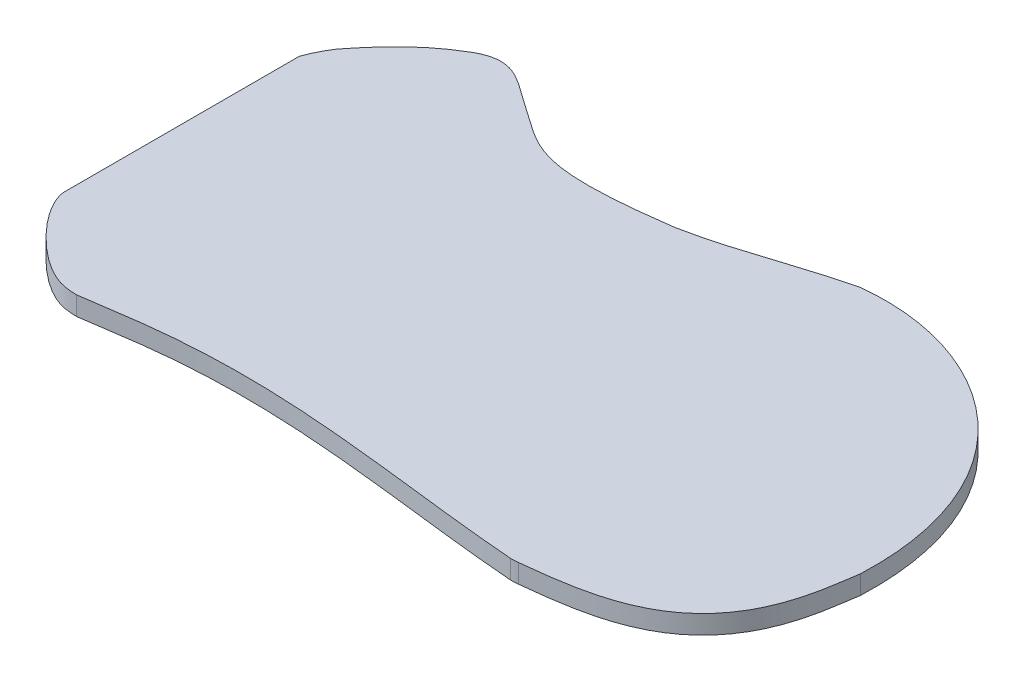
SolidWorks part; units mm, degrees
ref_plane "Front Plane" through (0, 0, 0) normal (0, 0, 1) x (1, 0, 0)
ref_plane "Top Plane" through (0, 0, 0) normal (0, 1, 0) x (1, 0, 0)
ref_plane "Right Plane" through (0, 0, 0) normal (1, 0, 0) x (0, 0, -1)
sketch "Sketch1" plane through (0, 0, 0) normal (0, 1, 0) x (1, 0, 0)
  line L0 (-78.6109, 24.9032) -> (-78.6109, -25.142)
  line L1 (78.526, -10.9955) -> (-78.6109, -10.9955) construction
  line L2 (-77.6109, 24.7348) -> (-77.6109, -25.142)
  line L3 (78.526, -11.9955) -> (-78.6109, -11.9955)
  arc A0 (37.4157, -46.3273) -> (39.1437, -46.2432) centre (37.8097, -36.6353) ccw
  arc A1 (37.4725, -45.3288) -> (39.0215, -45.2505) centre (37.8097, -36.6353) ccw
  spline S0 degree 3 poles (-77.6109, -25.142) (-77.6103, -25.4) (-77.563, -25.903) (-77.2897, -26.9857) (-76.6417, -28.5306) (-75.4978, -30.4481) (-73.6058, -33.039) (-70.8033, -36.112) (-67.3274, -39.127) (-64.1402, -41.244) (-61.4556, -42.4361) (-59.2812, -42.8778) (-58.0256, -42.9092) (-57.3728, -42.9466) knots 0.000484 0.000484 0.000484 0.000484 0.031521 0.062558 0.124632 0.186706 0.248781 0.372929 0.497077 0.621225 0.745373 0.869521 0.993669 0.993669 0.993669 0.993669
  spline S1 degree 3 poles (-57.3728, -42.9466) (-57.1306, -42.9172) (-56.6559, -42.8572) (-55.6329, -42.7168) (-54.2832, -42.5176) (-52.5297, -42.2482) (-50.0282, -41.8652) (-46.6003, -41.367) (-42.0363, -40.8111) (-37.0514, -40.3559) (-29.8812, -39.9429) (-20.0109, -39.8766) (-6.9377, -40.6174) (4.791, -41.8163) (14.5692, -42.9593) (22.0672, -43.8389) (29.7001, -44.6718) (34.8871, -45.1373) (37.4725, -45.3288) knots 0.000538 0.000538 0.000538 0.000538 0.016152 0.031766 0.062993 0.094221 0.125449 0.187904 0.250359 0.312815 0.37527 0.50018 0.625091 0.750001 0.812457 0.874912 0.937367 0.999822 0.999822 0.999822 0.999822
  spline S2 degree 3 poles (39.0215, -45.2505) (40.5541, -45.0873) (43.6362, -44.7445) (49.6297, -43.8727) (56.6431, -42.2158) (63.7646, -38.9137) (69.3225, -34.2155) (72.596, -29.3087) (74.4639, -25.0567) (75.5267, -21.803) (76.2971, -18.6022) (76.7457, -16.0939) (77.026, -14.2578) (77.207, -12.9947) (77.3723, -11.8407) (77.4763, -11.2132) (77.5311, -10.8821) knots -0.000309 -0.000309 -0.000309 -0.000309 0.063093 0.126495 0.253299 0.380104 0.506908 0.633712 0.697114 0.760516 0.823918 0.88732 0.919021 0.950722 0.982423 1.014124 1.014124 1.014124 1.014124
  spline S3 degree 3 poles (77.5311, -10.8821) (77.5748, -9.7665) (77.6099, -7.5074) (77.4888, -4.2729) (77.2058, -1.1252) (76.6195, 2.9373) (75.5088, 7.7538) (72.9895, 14.9059) (68.5668, 22.78) (61.5957, 30.4634) (53.3357, 36.3146) (44.1583, 40.2648) (34.4498, 42.2506) (27.8575, 42.2059) (24.6064, 41.8434) knots 0.000169 0.000169 0.000169 0.000169 0.031414 0.062658 0.093902 0.125147 0.187635 0.250124 0.375101 0.500079 0.625056 0.750034 0.875011 0.999988 0.999988 0.999988 0.999988
  spline S4 degree 3 poles (24.6064, 41.8434) (19.4417, 40.5996) (11.8686, 38.1019) (1.7069, 34.9414) (-3.4909, 33.6615) (-6.1131, 33.1605) knots 0.000659 0.000659 0.000659 0.000659 0.498067 0.746772 0.995476 0.995476 0.995476 0.995476
  spline S5 degree 3 poles (-6.1131, 33.1605) (-7.1417, 33.0163) (-9.1825, 32.742) (-13.4171, 32.237) (-18.6364, 31.7654) (-24.3553, 31.6023) (-29.2844, 31.96) (-33.4204, 32.9216) (-36.3715, 34.2616) (-38.6497, 35.6481) (-40.393, 36.836) (-41.9608, 37.95) (-43.3176, 38.8994) (-44.0701, 39.4107) (-44.4391, 39.6587) knots -0.000196 -0.000196 -0.000196 -0.000196 0.062587 0.12537 0.250936 0.376501 0.502067 0.627632 0.753198 0.815981 0.878764 0.941546 0.972938 1.004329 1.004329 1.004329 1.004329
  spline S6 degree 3 poles (-44.4391, 39.6587) (-44.6983, 39.8375) (-45.2219, 40.2027) (-46.2044, 40.9033) (-47.345, 41.7292) (-48.5998, 42.6198) (-50.1509, 43.6513) (-51.9146, 44.6189) (-53.8615, 45.2294) (-55.7055, 45.3275) (-57.1648, 45.051) (-58.2486, 44.6839) (-59.0003, 44.3616) (-59.6837, 44.0129) (-60.0375, 43.8061) (-60.2239, 43.694) knots -0.002497 -0.002497 -0.002497 -0.002497 0.029066 0.060629 0.123754 0.18688 0.250006 0.376257 0.502509 0.62876 0.755012 0.818137 0.881263 0.944389 1.007515 1.007515 1.007515 1.007515
  spline S7 degree 3 poles (-78.6109, -25.142) (-78.6097, -25.7822) (-78.3711, -27.0076) (-77.5216, -29.0127) (-76.3076, -31.0396) (-74.3365, -33.7283) (-71.4439, -36.8883) (-67.8634, -39.9802) (-64.5529, -42.1647) (-61.6917, -43.4202) (-59.6968, -43.8088) (-58.2959, -43.9054) (-57.6656, -43.9305) (-57.3419, -43.9502) knots 0.000409 0.000409 0.000409 0.000409 0.062843 0.125276 0.18771 0.250143 0.375011 0.499878 0.624745 0.749612 0.874479 0.936913 0.999346 0.999346 0.999346 0.999346
  spline S8 degree 3 poles (-57.3419, -43.9502) (-57.0965, -43.9206) (-56.6141, -43.8604) (-55.5847, -43.7202) (-54.2292, -43.5208) (-52.4771, -43.2519) (-49.983, -42.8696) (-46.5727, -42.3725) (-42.0367, -41.817) (-37.0824, -41.3612) (-29.9535, -40.9457) (-20.1287, -40.874) (-7.0907, -41.608) (4.6318, -42.8047) (14.4219, -43.9489) (21.9389, -44.8307) (29.5994, -45.6669) (34.8166, -46.135) (37.4157, -46.3273) knots -0.001373 -0.001373 -0.001373 -0.001373 0.014273 0.029919 0.06121 0.092502 0.123794 0.186377 0.24896 0.311543 0.374127 0.499293 0.62446 0.749626 0.81221 0.874793 0.937376 0.99996 0.99996 0.99996 0.99996
  spline S9 degree 3 poles (39.1437, -46.2432) (40.686, -46.0789) (43.7818, -45.7344) (49.848, -44.8507) (56.9964, -43.16) (64.3453, -39.7462) (70.1244, -34.8409) (73.5118, -29.7304) (75.4294, -25.3355) (76.5134, -21.9918) (77.2941, -18.7213) (77.7459, -16.1748) (78.0266, -14.3264) (78.2075, -13.0606) (78.3702, -11.9307) (78.4738, -11.3105) (78.5279, -10.984) knots -0.000086 -0.000086 -0.000086 -0.000086 0.063428 0.126941 0.253967 0.380993 0.50802 0.635046 0.698559 0.762072 0.825585 0.889098 0.920855 0.952612 0.984368 1.016125 1.016125 1.016125 1.016125
  spline S10 degree 3 poles (78.5279, -10.984) (78.5733, -9.8502) (78.6109, -7.5559) (78.4906, -4.2601) (78.2049, -1.0549) (77.6104, 3.0871) (76.4803, 8.0028) (73.9108, 15.31) (69.3901, 23.3646) (62.2582, 31.2245) (53.8088, 37.2052) (44.4261, 41.2372) (34.4991, 43.2588) (27.7571, 43.2053) (24.4331, 42.8302) knots -0.000407 -0.000407 -0.000407 -0.000407 0.03088 0.062166 0.093453 0.12474 0.187314 0.249888 0.375035 0.500183 0.62533 0.750478 0.875625 1.000773 1.000773 1.000773 1.000773
  spline S11 degree 3 poles (24.4331, 42.8302) (21.8301, 42.2051) (16.6685, 40.7402) (6.525, 37.4536) (-1.0744, 35.1413) (-6.2764, 34.1474) knots -0.001281 -0.001281 -0.001281 -0.001281 0.247714 0.49671 0.9947 0.9947 0.9947 0.9947
  spline S12 degree 3 poles (-6.2764, 34.1474) (-7.3001, 34.0039) (-9.3317, 33.7312) (-13.542, 33.2295) (-18.7181, 32.7628) (-24.3556, 32.604) (-29.1564, 32.9561) (-33.1061, 33.8787) (-35.9015, 35.1472) (-38.1022, 36.4854) (-39.8157, 37.6526) (-41.3786, 38.7631) (-42.7458, 39.7198) (-43.5043, 40.2353) (-43.8763, 40.4853) knots 0.000305 0.000305 0.000305 0.000305 0.063048 0.125791 0.251276 0.376761 0.502247 0.627732 0.753218 0.815961 0.878703 0.941446 0.972817 1.004189 1.004189 1.004189 1.004189
  spline S13 degree 3 poles (-43.8763, 40.4853) (-44.1324, 40.662) (-44.6496, 41.0228) (-45.6222, 41.7163) (-46.7618, 42.5415) (-48.0307, 43.4423) (-49.6264, 44.5037) (-51.4979, 45.535) (-53.6685, 46.2221) (-55.7733, 46.3353) (-57.4106, 46.0235) (-58.6015, 45.6208) (-59.4227, 45.2686) (-60.0246, 44.9622) (-60.4597, 44.7184) (-60.6399, 44.6107) (-60.7341, 44.5541) knots -0.002294 -0.002294 -0.002294 -0.002294 0.029245 0.060783 0.12386 0.186936 0.250013 0.376167 0.50232 0.628473 0.754627 0.817704 0.88078 0.943857 0.975396 1.006934 1.006934 1.006934 1.006934
  spline S14 degree 3 poles (-60.7341, 44.5541) (-61.1687, 44.2998) (-62.0358, 43.7712) (-63.676, 42.6889) (-66.3643, 40.7074) (-69.6969, 37.7112) (-72.4782, 34.663) (-74.193, 32.5981) (-75.1195, 31.4458) (-75.5587, 30.8903) (-75.7803, 30.6092) knots 0.000427 0.000427 0.000427 0.000427 0.063268 0.126109 0.251792 0.503158 0.754524 0.880206 0.943048 1.005889 1.005889 1.005889 1.005889
  spline S15 degree 3 poles (-60.2239, 43.694) (-60.6474, 43.4463) (-61.4924, 42.9314) (-63.0906, 41.8773) (-65.7124, 39.9465) (-68.9709, 37.0199) (-71.6981, 34.0358) (-73.6437, 31.6948) (-74.5236, 30.5881) (-74.9696, 30.0223) knots 0.000174 0.000174 0.000174 0.000174 0.062881 0.125589 0.251004 0.501833 0.752662 0.878077 1.003492 1.003492 1.003492 1.003492
  spline S16 degree 3 poles (-74.9696, 30.0223) (-75.5195, 29.1919) (-76.5302, 27.448) (-77.2874, 25.6577) (-77.6109, 24.7348) knots 0.499549 0.499549 0.499549 0.499549 0.499766 0.499983 0.499983 0.499983 0.499983
  spline S17 degree 3 poles (-75.7803, 30.6092) (-76.3738, 29.7162) (-77.4602, 27.8403) (-78.2688, 25.9015) (-78.6109, 24.9032) knots 0.499546 0.499546 0.499546 0.499546 0.49977 0.499995 0.499995 0.499995 0.499995
  point P0 (0.0094, -10.9955)
extrude "Boss-Extrude2" add sketch "Sketch1" along normal blind 4 contours L1 S2 S3 S4 S5 S6 S15 S16 L2 | S2 L1 L2 L3 | A1 S2 L3 L2 S0 S1
ref_plane "Plane1" through (0, 0, -24.7348) normal (0, 0, -1) x (0, -1, 0)
sketch "Sketch2" plane through (0, 4, 0) normal (0, 1, 0) x (1, 0, 0)
  circle A0 centre (-52.6013, 19.445) radius 6
extrude "Boss-Extrude3" add sketch "Sketch2" along normal blind 2.5
sketch "Sketch4" plane through (0, 6.5, 0) normal (0, 1, 0) x (1, 0, 0)
  circle A0 centre (-52.6013, 19.445) radius 2.5
extrude "Cut-Extrude1" cut sketch "Sketch4" against normal blind 2.5
pattern_linear "LPattern1" count 3 spacing 20 along (0, 0, 1) count 6 spacing 20 along (1, 0, 0) of "Cut-Extrude1", "Boss-Extrude3"
ref_plane "Plane2" through (0, 0, 0) normal (0, -1, 0) x (-1, 0, 0)
mirror "Mirror1" about plane through (0, 0, 0) normal (0, -1, 0) of "LPattern1", "Cut-Extrude1", "Boss-Extrude3", "Boss-Extrude2"
sketch "Sketch5" plane through (0, 6.5, 0) normal (0, 1, 0) x (1, 0, 0)
  line L1 (-109.7037, 76.0627) -> (107.3614, 76.0627)
  line L2 (-109.7037, 76.0627) -> (-109.7037, -76.7368)
  line L3 (-109.7037, -76.7368) -> (107.3614, -76.7368)
  line L4 (107.3614, 76.0627) -> (107.3614, -76.7368)
extrude "Cut-Extrude2" cut sketch "Sketch5" against normal up to surface (6.5 mm away)
